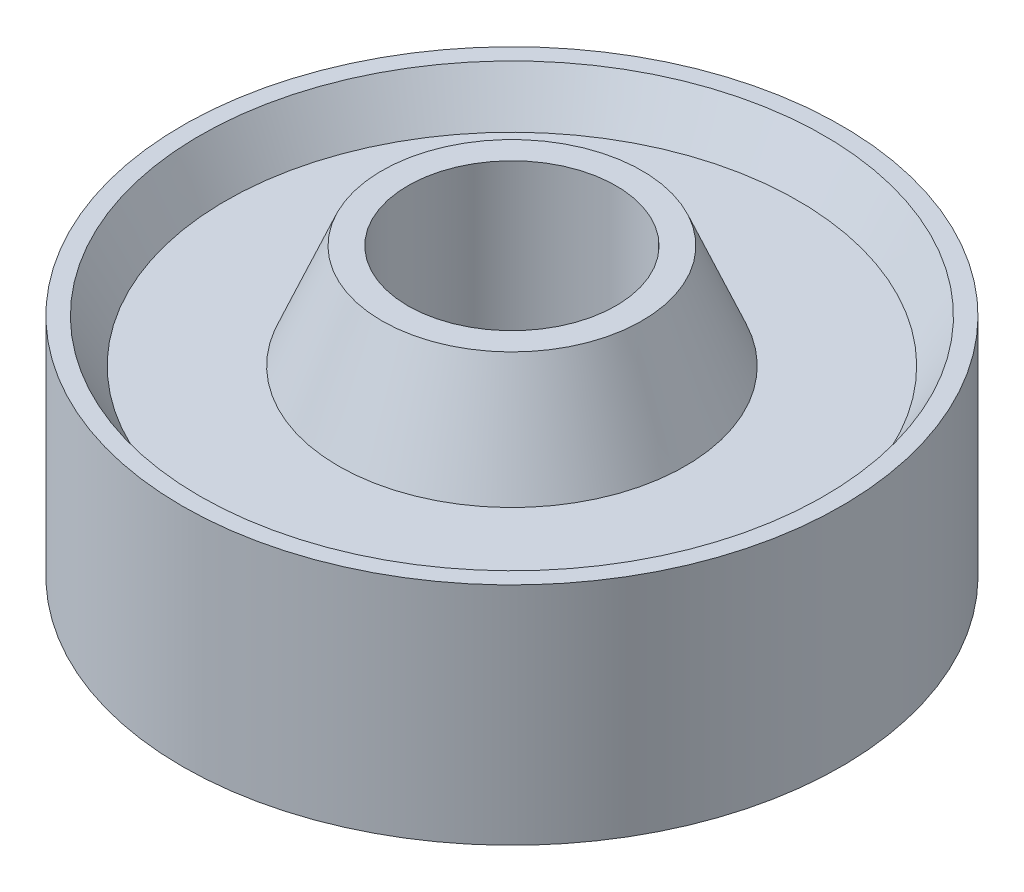
SolidWorks part; units mm, degrees
ref_plane "Front Plane" through (0, 0, 0) normal (0, 0, 1) x (1, 0, 0)
ref_plane "Top Plane" through (0, 0, 0) normal (0, 1, 0) x (1, 0, 0)
ref_plane "Right Plane" through (0, 0, 0) normal (1, 0, 0) x (0, 0, -1)
sketch "Sketch1" plane through (0, 0, 0) normal (0, 0, 1) x (1, 0, 0)
  line L0 (0, 74.9161) -> (0, 20) construction
  line L1 (0, 20) -> (15, 20)
  line L2 (15, 20) -> (20, 8)
  line L3 (20, 8) -> (33, 8)
  line L4 (33, 8) -> (36, 13)
  line L5 (36, 13) -> (38, 13)
  line L6 (38, 13) -> (38, -13)
  line L13 (-7.746, 0) -> (61.5126, 0) construction
  line L14 (0, 20) -> (0, -20)
  line L15 (36, -13) -> (38, -13)
  line L16 (33, -8) -> (36, -13)
  line L17 (20, -8) -> (33, -8)
  line L18 (15, -20) -> (20, -8)
  line L19 (0, -20) -> (15, -20)
  point P1 (26.8833, 0)
  point P11 (38, 0)
  point P19 (0, 0)
  dimension "D1" = 20
  dimension "12" = 15
  dimension "D2" = 20
  dimension "D3" = 13
  dimension "2" = 2
  dimension "D4" = 8
  dimension "D5" = 33
  dimension "D6" = 38
revolve "Revolve1" add sketch "Sketch1" angle 360 about L14
sketch "Sketch2" plane through (0, 20, 0) normal (0, 1, 0) x (1, 0, 0)
  circle A0 centre (0, 0) radius 12
  dimension "D1" = 24
extrude "Cut-Extrude1" cut sketch "Sketch2" against normal through all
